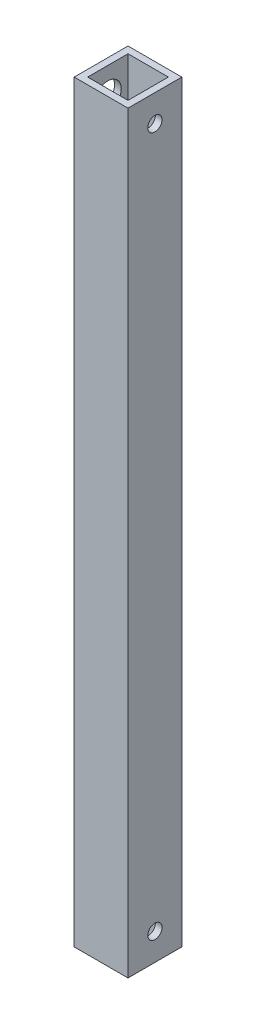
SolidWorks part; units mm, degrees
ref_plane "Front Plane" through (0, 0, 0) normal (0, 0, 1) x (1, 0, 0)
ref_plane "Top Plane" through (0, 0, 0) normal (0, 1, 0) x (1, 0, 0)
ref_plane "Right Plane" through (0, 0, 0) normal (1, 0, 0) x (0, 0, -1)
sketch "Sketch1" plane through (0, 0, 0) normal (0, 1, 0) x (1, 0, 0)
  line L0 (3.175, 3.175) -> (3.175, 22.225)
  line L1 (0, 0) -> (25.4, 0)
  line L2 (0, 0) -> (0, 25.4)
  line L3 (0, 25.4) -> (25.4, 25.4)
  line L4 (25.4, 0) -> (25.4, 25.4)
  line L5 (3.175, 22.225) -> (22.225, 22.225)
  line L6 (22.225, 3.175) -> (22.225, 22.225)
  line L7 (3.175, 3.175) -> (22.225, 3.175)
  dimension "D1" = 25.4
  dimension "D2" = 25.4
  dimension "D3" = 3.175
extrude "Boss-Extrude1" add sketch "Sketch1" along normal blind 355.6
sketch "Sketch2" plane through (25.4, 0, 0) normal (1, 0, 0) x (0, 0, -1)
  line L0 (25.4, 355.6) -> (25.4, 0) construction
  line L1 (13.97, 0) -> (-13.97, 0) construction
  circle A0 centre (12.7, 12.7) radius 3.3734
  dimension "D1" = 6.7469
  dimension "D2" = 12.7
  dimension "D3" = 12.7
extrude "Cut-Extrude1" cut sketch "Sketch2" against normal through all
ref_plane "Plane1" through (0, 177.8, 0) normal (0, 1, 0) x (1, 0, 0)
mirror "Mirror1" about plane through (0, 177.8, 0) normal (0, 1, 0) of "Cut-Extrude1"
sketch "Sketch3" plane through (0, 0, 0) normal (-1, 0, 0) x (0, 0, 1)
  circle A0 centre (-12.7, 342.9) radius 6.35
  circle A1 centre (-12.7, 12.7) radius 6.35
  dimension "D1" = 12.7
extrude "Cut-Extrude2" cut sketch "Sketch3" against normal up to next
